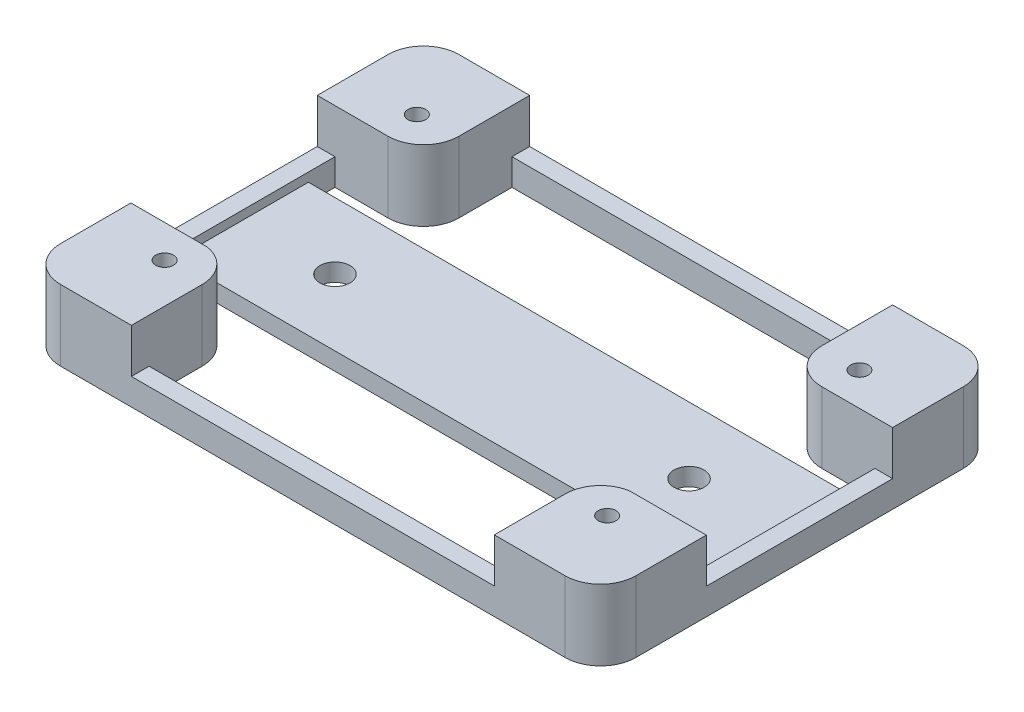
SolidWorks part; units mm, degrees
ref_plane "Front Plane" through (0, 0, 0) normal (0, 0, 1) x (1, 0, 0)
ref_plane "Top Plane" through (0, 0, 0) normal (0, 1, 0) x (1, 0, 0)
ref_plane "Right Plane" through (0, 0, 0) normal (1, 0, 0) x (0, 0, -1)
sketch "Sketch1" plane through (0, 0, 0) normal (0, 1, 0) x (1, 0, 0)
  line L0 (-30.5, 10.5) -> (-30.5, -10.5)
  line L1 (-28.5, 22.5) -> (28.5, 22.5)
  line L2 (-32.5, 18.5) -> (-32.5, -18.5)
  line L3 (-28.5, -22.5) -> (28.5, -22.5)
  line L4 (32.5, 18.5) -> (32.5, -18.5)
  line L5 (-32.5, 22.5) -> (32.5, -22.5) construction
  line L6 (-32.5, -22.5) -> (32.5, 22.5) construction
  line L7 (-20.5, -20.5) -> (20.5, -20.5)
  line L8 (30.5, 10.5) -> (30.5, -10.5)
  line L9 (-20.5, 20.5) -> (20.5, 20.5)
  line L10 (-30.5, 10.5) -> (-24.5, 10.5)
  line L11 (-25, 14.25) -> (25, 14.25) construction
  line L12 (-25, 14.25) -> (-25, -14.25) construction
  line L13 (-25, -14.25) -> (25, -14.25) construction
  line L14 (25, 14.25) -> (25, -14.25) construction
  line L15 (-25, 14.25) -> (25, -14.25) construction
  line L16 (-25, -14.25) -> (25, 14.25) construction
  line L17 (-20.5, 14.5) -> (-20.5, 20.5)
  line L18 (20.5, 20.5) -> (20.5, 14.5)
  line L19 (24.5, 10.5) -> (30.5, 10.5)
  line L20 (-30.5, -10.5) -> (-24.5, -10.5)
  line L21 (-20.5, -14.5) -> (-20.5, -20.5)
  line L22 (30.5, -10.5) -> (24.5, -10.5)
  line L23 (20.5, -14.5) -> (20.5, -20.5)
  line L24 (-30.5, 18.5) -> (-30.5, -18.5) construction
  line L25 (-28.5, -20.5) -> (28.5, -20.5) construction
  line L26 (30.5, 18.5) -> (30.5, -18.5) construction
  line L27 (-28.5, 20.5) -> (28.5, 20.5) construction
  arc A0 (32.5, 18.5) -> (28.5, 22.5) centre (28.5, 18.5) ccw
  arc A1 (28.5, -22.5) -> (32.5, -18.5) centre (28.5, -18.5) ccw
  arc A2 (-28.5, -22.5) -> (-32.5, -18.5) centre (-28.5, -18.5) cw
  arc A3 (-32.5, 18.5) -> (-28.5, 22.5) centre (-28.5, 18.5) cw
  circle A8 centre (-25, 14.25) radius 1
  circle A9 centre (25, 14.25) radius 1
  circle A10 centre (25, -14.25) radius 1
  circle A11 centre (-25, -14.25) radius 1
  arc A12 (-28.5, -20.5) -> (-30.5, -18.5) centre (-28.5, -18.5) cw construction
  arc A13 (28.5, -20.5) -> (30.5, -18.5) centre (28.5, -18.5) ccw construction
  arc A14 (30.5, 18.5) -> (28.5, 20.5) centre (28.5, 18.5) ccw construction
  arc A15 (-30.5, 18.5) -> (-28.5, 20.5) centre (-28.5, 18.5) cw construction
  arc A16 (-20.5, -14.5) -> (-24.5, -10.5) centre (-24.5, -14.5) ccw
  arc A17 (20.5, -14.5) -> (24.5, -10.5) centre (24.5, -14.5) cw
  arc A18 (24.5, 10.5) -> (20.5, 14.5) centre (24.5, 14.5) cw
  arc A19 (-20.5, 14.5) -> (-24.5, 10.5) centre (-24.5, 14.5) cw
  point P0 (0, 0)
  point P30 (0, 0)
  point P53 (-20.5, -10.5)
  point P56 (20.5, -10.5)
  point P59 (20.5, 10.5)
  point P62 (-20.5, 10.5)
  dimension "D3" = 4
  dimension "D7" = 10
  dimension "D15" = 4
  dimension "D1" = 65
  dimension "D2" = 45
  dimension "D5" = 50
  dimension "D6" = 28.5
  dimension "D8" = 10
  dimension "D9" = 10
  dimension "D10" = 10
  dimension "D11" = 10
  dimension "D12" = 10
  dimension "D13" = 10
  dimension "D14" = 10
  dimension "D4" = 2
extrude "Boss-Extrude1" add sketch "Sketch1" along normal blind 8
sketch "Sketch2" plane through (0, 0, 0) normal (0, 1, 0) x (1, 0, 0)
  line L1 (-31.5, -7.5) -> (31.5, -7.5)
  line L2 (-31.5, -7.5) -> (-31.5, 7.5)
  line L3 (-31.5, 7.5) -> (31.5, 7.5)
  line L4 (31.5, -7.5) -> (31.5, 7.5)
  line L5 (-31.5, -7.5) -> (31.5, 7.5) construction
  line L6 (-31.5, 7.5) -> (31.5, -7.5) construction
  point P0 (0, 0)
  dimension "D1" = 15
  dimension "D2" = 63
extrude "Boss-Extrude2" add sketch "Sketch2" along normal blind 2
sketch "Sketch3" plane through (0, 2, 0) normal (0, 1, 0) x (1, 0, 0)
  circle A0 centre (-20, 0) radius 1.7
  circle A1 centre (20, 0) radius 1.7
  dimension "D1" = 3.4
  dimension "D2" = 3.4
  dimension "D3" = 20
  dimension "D4" = 20
extrude "Cut-Extrude1" cut sketch "Sketch3" against normal blind 2
sketch "Sketch4" plane through (0, 8, 0) normal (0, 1, 0) x (1, 0, 0)
  line L0 (28.5, 22.5) -> (-28.5, 22.5) construction
  line L1 (-20.5, 22.5) -> (20.5, 22.5)
  line L2 (-20.5, 22.5) -> (-20.5, -22.5)
  line L3 (-20.5, -22.5) -> (20.5, -22.5)
  line L4 (20.5, 22.5) -> (20.5, -22.5)
  line L5 (-28.5, -22.5) -> (28.5, -22.5) construction
extrude "Cut-Extrude2" cut sketch "Sketch4" against normal blind 5
sketch "Sketch5" plane through (0, 8, 0) normal (0, 1, 0) x (1, 0, 0)
  line L0 (-32.5, 18.5) -> (-32.5, -18.5) construction
  line L1 (-32.5, 10.5) -> (32.5, 10.5)
  line L2 (-32.5, 10.5) -> (-32.5, -10.5519)
  line L3 (-32.5, -10.5519) -> (32.5, -10.5519)
  line L4 (32.5, 10.5) -> (32.5, -10.5519)
  line L5 (32.5, -18.5) -> (32.5, 18.5) construction
extrude "Cut-Extrude3" cut sketch "Sketch5" against normal blind 5
